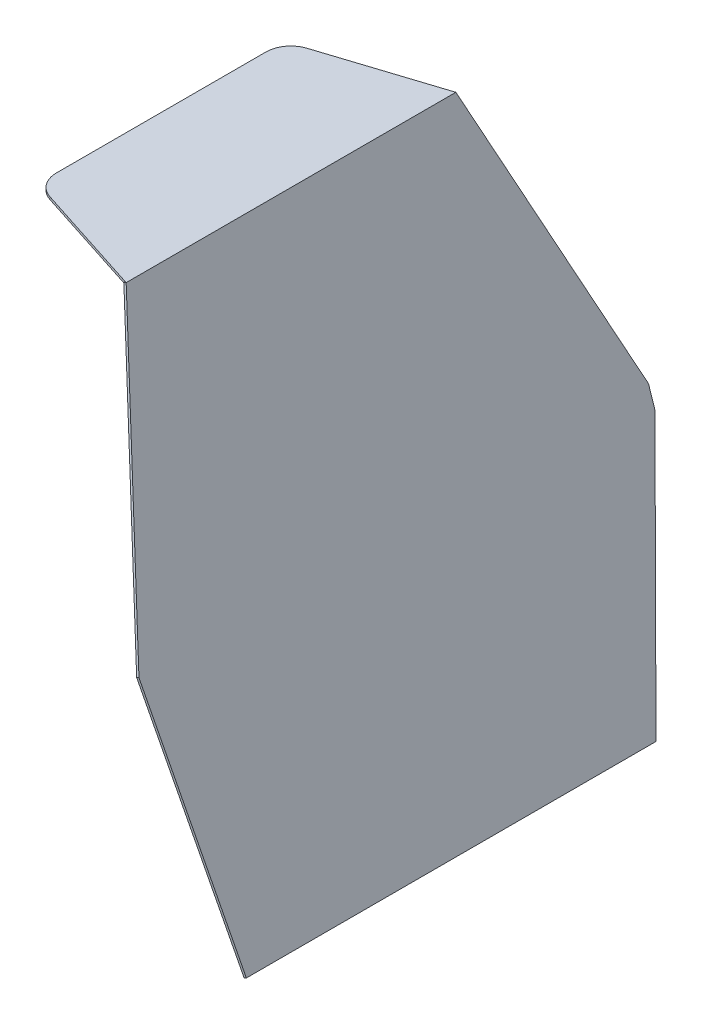
SolidWorks part; units mm, degrees
ref_plane "Front Plane" through (0, 0, 0) normal (0, 0, 1) x (1, 0, 0)
ref_plane "Top Plane" through (0, 0, 0) normal (0, 1, 0) x (1, 0, 0)
ref_plane "Right Plane" through (0, 0, 0) normal (1, 0, 0) x (0, 0, -1)
sketch "Sketch2" plane through (0, 0, 0) normal (1, 0, 0) x (0, 0, -1)
  line L0 (0, 0) -> (609.6, 0) construction
  line L1 (55, 0) -> (-55, 0) construction
  point P5 (464.6739, 193.0622)
  point P7 (304.8, 0)
  dimension "D1" = 609.6
ref_plane "Plane2" through (0, 0, 0) normal (0.9227, 0.3854, 0) x (0, 0, -1)
sketch "Sketch3" plane through (0, 0, 0) normal (0.9227, 0.3854, 0) x (0, 0, -1)
  line L0 (0, 0) -> (609.6, 0)
  line L1 (609.6, 0) -> (628.65, 304.8)
  line L2 (628.65, 304.8) -> (514.35, 643.5822)
  line L3 (514.35, 643.5822) -> (95.25, 643.5822)
  line L4 (95.25, 643.5822) -> (-19.05, 304.8)
  line L5 (-19.05, 304.8) -> (0, 0)
  line L6 (304.8, 643.5822) -> (304.8, 0) construction
  line L7 (-19.05, 304.8) -> (628.65, 304.8) construction
  dimension "D1" = 647.7
  dimension "D2" = 609.6
  dimension "D3" = 338.7822
  dimension "D4" = 304.8
  dimension "D5" = 419.1
extrude "Boss-Extrude2" add sketch "Sketch3" along normal blind 3.175
ref_plane "Plane3" through (0, 595.0827, 0) normal (0, 1, 0) x (1, 0, 0)
sketch "Sketch4" plane through (0, 595.0827, 0) normal (0, 1, 0) x (1, 0, 0)
  line L1 (-245.1216, 514.35) -> (-388.2144, 468.215)
  line L2 (-245.1216, 514.35) -> (-245.1216, 95.25)
  line L3 (-245.1216, 95.25) -> (-388.2144, 141.385)
  line L4 (-410.2216, 437.9968) -> (-410.2216, 171.6032)
  arc A0 (-388.2144, 468.215) -> (-410.2216, 437.9968) centre (-378.4716, 437.9968) ccw
  arc A1 (-410.2216, 171.6032) -> (-388.2144, 141.385) centre (-378.4716, 171.6032) ccw
  dimension "D3" = 31.75
  dimension "D1" = 165.1
  dimension "D2" = 35.74
extrude "Boss-Extrude3" add sketch "Sketch4" against normal blind 3.175
sketch "Sketch5" plane through (0, 0, 0) normal (0.9227, 0.3854, 0) x (0, 0, -1)
  line L0 (609.6, 0) -> (627.0625, 279.4)
  line L1 (609.6, 0) -> (628.65, 304.8) construction
  line L2 (627.0625, 279.4) -> (520.7, 0)
  line L3 (0, 0) -> (609.6, 0) construction
  line L4 (520.7, 0) -> (609.6, 0)
  dimension "D1" = 88.9
  dimension "D2" = 279.4
extrude "Cut-Extrude2" cut sketch "Sketch5" along normal through all
